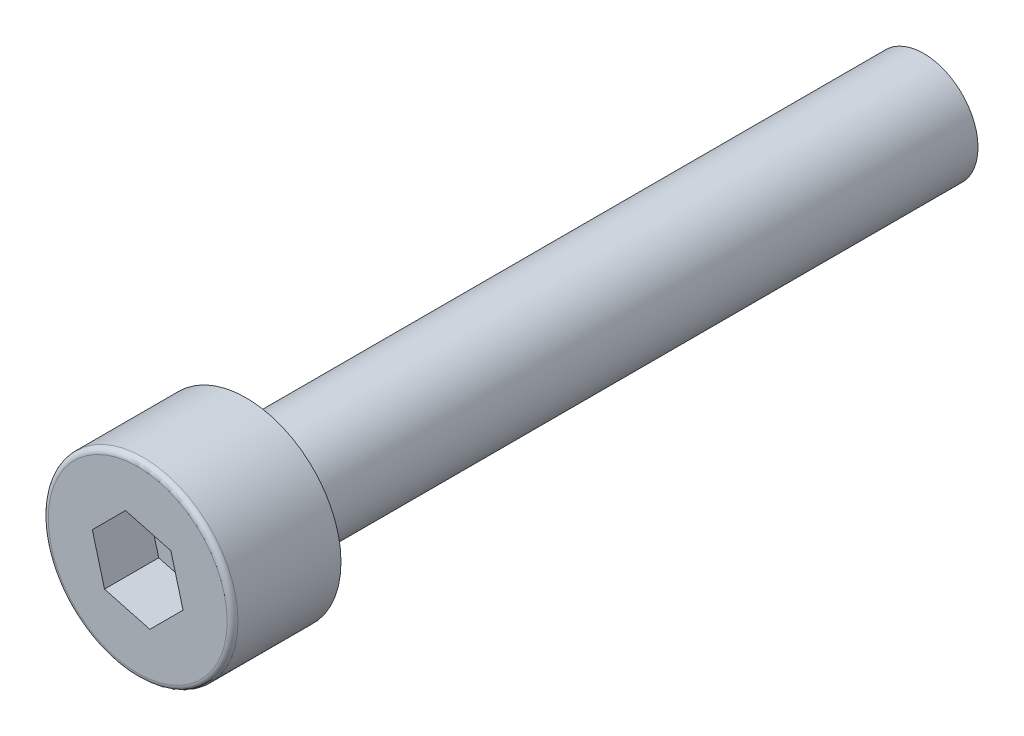
SolidWorks part; units mm, degrees
ref_plane "前视基准面" through (0, 0, 0) normal (0, 0, 1) x (1, 0, 0)
ref_plane "上视基准面" through (0, 0, 0) normal (0, 1, 0) x (1, 0, 0)
ref_plane "右视基准面" through (0, 0, 0) normal (1, 0, 0) x (0, 0, -1)
sketch "草图1" plane through (0, 0, 0) normal (0, 0, 1) x (1, 0, 0)
  circle A0 centre (0, 0) radius 3.5
  dimension "D1" = 7
extrude "凸台-拉伸1" add sketch "草图1" along normal blind 4
sketch "草图2" plane through (0, 0, 4) normal (0, 0, 1) x (1, 0, 0)
  line L1 (-1.2247, -1.2247) -> (0.4483, -1.673)
  line L2 (0.4483, -1.673) -> (1.673, -0.4483)
  line L3 (1.673, -0.4483) -> (1.2247, 1.2247)
  line L4 (1.2247, 1.2247) -> (-0.4483, 1.673)
  line L5 (-0.4483, 1.673) -> (-1.673, 0.4483)
  line L6 (-1.673, 0.4483) -> (-1.2247, -1.2247)
  circle A0 centre (0, 0) radius 1.5 construction
  dimension "D1" = 3
extrude "切除-拉伸1" cut sketch "草图2" against normal blind 2
sketch "草图3" plane through (0, 0, 0) normal (0, 0, -1) x (-1, 0, 0)
  circle A0 centre (0, 0) radius 2
  dimension "D1" = 4
extrude "凸台-拉伸2" add sketch "草图3" along normal blind 25
fillet "圆角1" radius 0.2 1 edges at (3.5, 0, 4)
